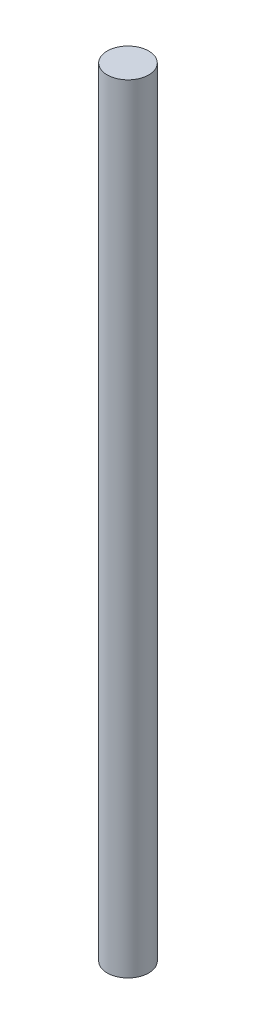
SolidWorks part; units mm, degrees
ref_plane "Front Plane" through (0, 0, 0) normal (0, 0, 1) x (1, 0, 0)
ref_plane "Top Plane" through (0, 0, 0) normal (0, 1, 0) x (1, 0, 0)
ref_plane "Right Plane" through (0, 0, 0) normal (1, 0, 0) x (0, 0, -1)
sketch "Sketch1" plane through (0, 0, 0) normal (0, 1, 0) x (1, 0, 0)
  circle A0 centre (0, 0) radius 25.4
  dimension "D1" = 50.8
extrude "Boss-Extrude1" add sketch "Sketch1" along normal blind 952.5
